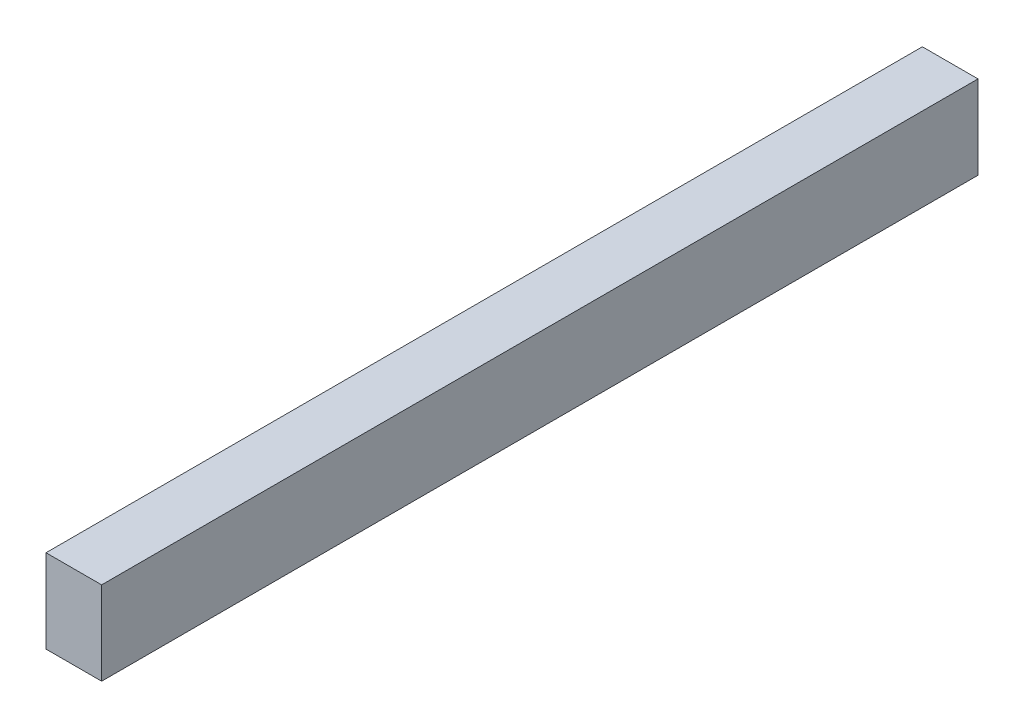
SolidWorks part; units mm, degrees
ref_plane "Front Plane" through (0, 0, 0) normal (0, 0, 1) x (1, 0, 0)
ref_plane "Top Plane" through (0, 0, 0) normal (0, 1, 0) x (1, 0, 0)
ref_plane "Right Plane" through (0, 0, 0) normal (1, 0, 0) x (0, 0, -1)
sketch "Sketch1" plane through (0, 0, 0) normal (1, 0, 0) x (0, 0, -1)
  line L1 (-31.5, -3) -> (31.5, -3)
  line L2 (-31.5, -3) -> (-31.5, 3)
  line L3 (-31.5, 3) -> (31.5, 3)
  line L4 (31.5, -3) -> (31.5, 3)
  line L5 (-31.5, -3) -> (31.5, 3) construction
  line L6 (-31.5, 3) -> (31.5, -3) construction
  point P0 (0, 0)
  dimension "D1" = 6
  dimension "D2" = 63
extrude "Boss-Extrude1" add sketch "Sketch1" along normal blind 4
